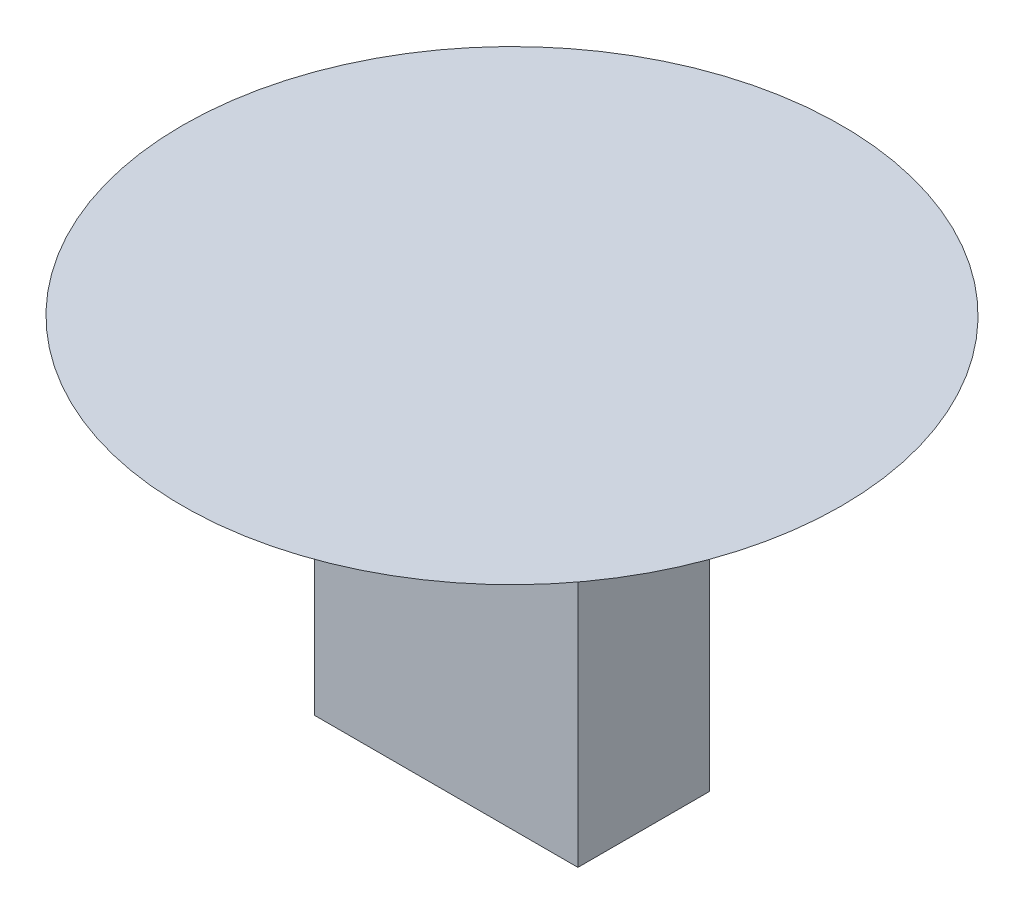
SolidWorks part; units mm, degrees
material "ABS"
ref_plane "前视基准面" through (0, 0, 0) normal (0, 0, 1) x (1, 0, 0)
ref_plane "上视基准面" through (0, 0, 0) normal (0, 1, 0) x (1, 0, 0)
ref_plane "右视基准面" through (0, 0, 0) normal (1, 0, 0) x (0, 0, -1)
other "Configuration Table"
sketch "草图1" plane through (0, 0, 0) normal (0, 1, 0) x (1, 0, 0)
  line L1 (-80, 40) -> (80, 40)
  line L2 (-80, 40) -> (-80, -40)
  line L3 (-80, -40) -> (80, -40)
  line L4 (80, 40) -> (80, -40)
  line L5 (-80, 40) -> (80, -40) construction
  line L6 (-80, -40) -> (80, 40) construction
  point P0 (0, 0)
  dimension "D1" = 80
  dimension "D2" = 160
extrude "凸台-拉伸1" add sketch "草图1" along normal blind 200
sketch "草图2" plane through (0, 0, 0) normal (0, 0, 1) x (1, 0, 0)
  line L0 (0, 200) -> (0, 230) construction
  line L1 (-80, 200) -> (80, 200) construction
  line L7 (0, 242.5969) -> (0, 230) construction
  line L8 (0, 138.3292) -> (0, -15.9963) construction
  line L9 (0, 138.3292) -> (0, -25.4742) construction
  line L10 (0, 230) -> (-200, 230)
  line L11 (-200, 230) -> (-80, 200)
  line L12 (-80, 200) -> (0, 200)
  line L13 (0, 200) -> (0, 230)
  dimension "D1" = 30
  dimension "D2" = 200
revolve "旋转1" add sketch "草图2" angle 360 about L7
